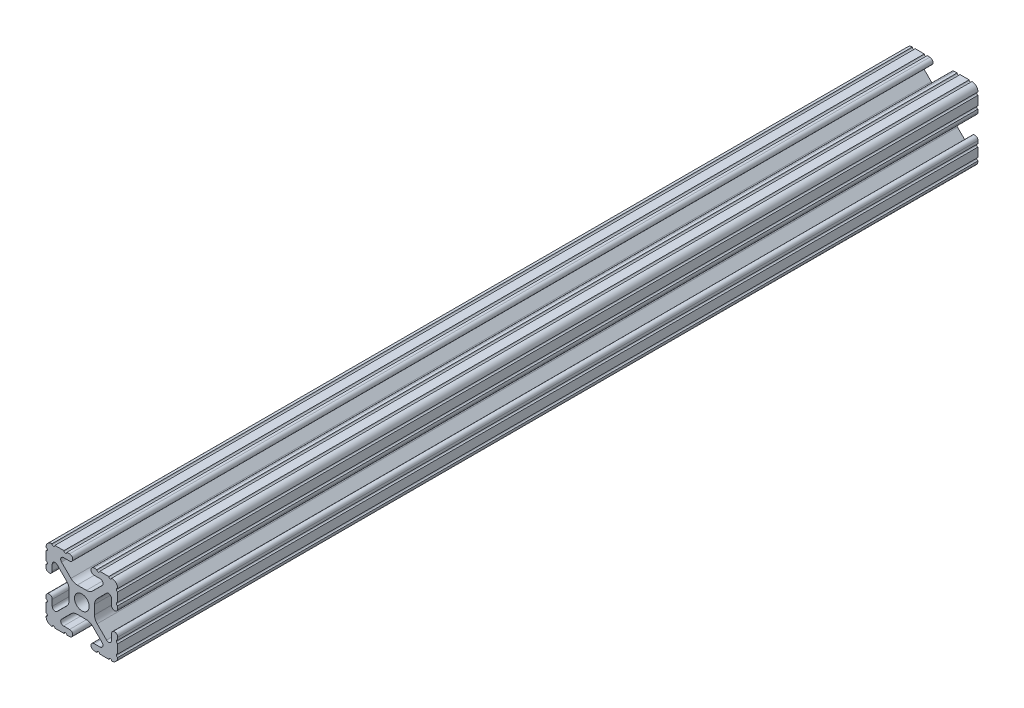
SolidWorks part; units mm, degrees
ref_plane "Front Plane" through (0, 0, 0) normal (0, 0, 1) x (1, 0, 0)
ref_plane "Top Plane" through (0, 0, 0) normal (0, 1, 0) x (1, 0, 0)
ref_plane "Right Plane" through (0, 0, 0) normal (1, 0, 0) x (0, 0, -1)
ref_plane "Plane1" through (0, 0, -25.4) normal (0, 0, -1) x (-1, 0, 0)
sketch "Sketch1" plane through (0, 0, -25.4) normal (0, 0, -1) x (-1, 0, 0)
  line L0 (12.7, -9.5504) -> (12.7, -6.3331)
  line L1 (12.7, -5.3171) -> (12.7, -4.3434)
  line L2 (10.4902, -4.3434) -> (10.4902, -6.4748)
  line L3 (8.7558, -7.1932) -> (5.4257, -3.8632)
  line L4 (4.4958, -1.6181) -> (4.4958, 1.6181)
  line L5 (5.4257, 3.8632) -> (8.7558, 7.1932)
  line L6 (10.4902, 6.4748) -> (10.4902, 4.3434)
  line L7 (12.7, 4.3434) -> (12.7, 5.3171)
  line L8 (12.7, 6.3331) -> (12.7, 9.5504)
  line L9 (9.5504, 12.7) -> (6.3331, 12.7)
  line L10 (5.3171, 12.7) -> (4.3434, 12.7)
  line L11 (4.3434, 10.4902) -> (6.4748, 10.4902)
  line L12 (7.1932, 8.7558) -> (3.8632, 5.4257)
  line L13 (1.6181, 4.4958) -> (-1.6181, 4.4958)
  line L14 (-3.8632, 5.4257) -> (-7.1932, 8.7558)
  line L15 (-6.4748, 10.4902) -> (-4.3434, 10.4902)
  line L16 (-4.3434, 12.7) -> (-5.3171, 12.7)
  line L17 (-6.3331, 12.7) -> (-9.5504, 12.7)
  line L18 (-12.7, 9.5504) -> (-12.7, 6.3331)
  line L19 (-12.7, 5.3171) -> (-12.7, 4.3434)
  line L20 (-10.4902, 4.3434) -> (-10.4902, 6.4748)
  line L21 (-8.7558, 7.1932) -> (-5.4257, 3.8632)
  line L22 (-4.4958, 1.6181) -> (-4.4958, -1.6181)
  line L23 (-5.4257, -3.8632) -> (-8.7558, -7.1932)
  line L24 (-10.4902, -6.4748) -> (-10.4902, -4.3434)
  line L25 (-12.7, -4.3434) -> (-12.7, -5.3171)
  line L26 (-12.7, -6.3331) -> (-12.7, -9.5504)
  line L27 (-9.5504, -12.7) -> (-6.3331, -12.7)
  line L28 (-5.3171, -12.7) -> (-4.3434, -12.7)
  line L29 (-4.3434, -10.4902) -> (-6.4748, -10.4902)
  line L30 (-7.1932, -8.7558) -> (-3.8632, -5.4257)
  line L31 (-1.6181, -4.4958) -> (1.6181, -4.4958)
  line L32 (3.8632, -5.4257) -> (7.1932, -8.7558)
  line L33 (6.4748, -10.4902) -> (4.3434, -10.4902)
  line L34 (4.3434, -12.7) -> (5.3171, -12.7)
  line L35 (6.3331, -12.7) -> (9.5504, -12.7)
  arc A0 (12.6998, -10.5664) -> (12.7, -9.5504) centre (12.7, -10.0584) cw
  arc A1 (12.7, -6.3331) -> (12.7, -5.3171) centre (12.7, -5.8251) cw
  arc A2 (12.7, -4.3434) -> (10.4902, -4.3434) centre (11.5951, -4.3434) ccw
  arc A3 (10.4902, -6.4748) -> (8.7558, -7.1932) centre (9.4742, -6.4748) cw
  arc A4 (5.4257, -3.8632) -> (4.4958, -1.6181) centre (7.6708, -1.6181) cw
  arc A5 (4.4958, 1.6181) -> (5.4257, 3.8632) centre (7.6708, 1.6181) cw
  arc A6 (8.7558, 7.1932) -> (10.4902, 6.4748) centre (9.4742, 6.4748) cw
  arc A7 (10.4902, 4.3434) -> (12.7, 4.3434) centre (11.5951, 4.3434) ccw
  arc A8 (12.7, 5.3171) -> (12.7, 6.3331) centre (12.7, 5.8251) cw
  arc A9 (12.7, 9.5504) -> (12.6998, 10.5664) centre (12.7, 10.0584) cw
  arc A10 (12.6998, 10.5664) -> (10.5664, 12.6998) centre (10.5918, 10.5918) ccw
  arc A11 (10.5664, 12.6998) -> (9.5504, 12.7) centre (10.0584, 12.7) cw
  arc A12 (6.3331, 12.7) -> (5.3171, 12.7) centre (5.8251, 12.7) cw
  arc A13 (4.3434, 12.7) -> (4.3434, 10.4902) centre (4.3434, 11.5951) ccw
  arc A14 (6.4748, 10.4902) -> (7.1932, 8.7558) centre (6.4748, 9.4742) cw
  arc A15 (3.8632, 5.4257) -> (1.6181, 4.4958) centre (1.6181, 7.6708) cw
  arc A16 (-1.6181, 4.4958) -> (-3.8632, 5.4257) centre (-1.6181, 7.6708) cw
  arc A17 (-7.1932, 8.7558) -> (-6.4748, 10.4902) centre (-6.4748, 9.4742) cw
  arc A18 (-4.3434, 10.4902) -> (-4.3434, 12.7) centre (-4.3434, 11.5951) ccw
  arc A19 (-5.3171, 12.7) -> (-6.3331, 12.7) centre (-5.8251, 12.7) cw
  arc A20 (-9.5504, 12.7) -> (-10.5664, 12.6998) centre (-10.0584, 12.7) cw
  arc A21 (-10.5664, 12.6998) -> (-12.6998, 10.5664) centre (-10.5918, 10.5918) ccw
  arc A22 (-12.6998, 10.5664) -> (-12.7, 9.5504) centre (-12.7, 10.0584) cw
  arc A23 (-12.7, 6.3331) -> (-12.7, 5.3171) centre (-12.7, 5.8251) cw
  arc A24 (-12.7, 4.3434) -> (-10.4902, 4.3434) centre (-11.5951, 4.3434) ccw
  arc A25 (-10.4902, 6.4748) -> (-8.7558, 7.1932) centre (-9.4742, 6.4748) cw
  arc A26 (-5.4257, 3.8632) -> (-4.4958, 1.6181) centre (-7.6708, 1.6181) cw
  arc A27 (-4.4958, -1.6181) -> (-5.4257, -3.8632) centre (-7.6708, -1.6181) cw
  arc A28 (-8.7558, -7.1932) -> (-10.4902, -6.4748) centre (-9.4742, -6.4748) cw
  arc A29 (-10.4902, -4.3434) -> (-12.7, -4.3434) centre (-11.5951, -4.3434) ccw
  arc A30 (-12.7, -5.3171) -> (-12.7, -6.3331) centre (-12.7, -5.8251) cw
  arc A31 (-12.7, -9.5504) -> (-12.6998, -10.5664) centre (-12.7, -10.0584) cw
  arc A32 (-12.6998, -10.5664) -> (-10.5664, -12.6998) centre (-10.5918, -10.5918) ccw
  arc A33 (-10.5664, -12.6998) -> (-9.5504, -12.7) centre (-10.0584, -12.7) cw
  arc A34 (-6.3331, -12.7) -> (-5.3171, -12.7) centre (-5.8251, -12.7) cw
  arc A35 (-4.3434, -12.7) -> (-4.3434, -10.4902) centre (-4.3434, -11.5951) ccw
  arc A36 (-6.4748, -10.4902) -> (-7.1932, -8.7558) centre (-6.4748, -9.4742) cw
  arc A37 (-3.8632, -5.4257) -> (-1.6181, -4.4958) centre (-1.6181, -7.6708) cw
  arc A38 (1.6181, -4.4958) -> (3.8632, -5.4257) centre (1.6181, -7.6708) cw
  arc A39 (7.1932, -8.7558) -> (6.4748, -10.4902) centre (6.4748, -9.4742) cw
  arc A40 (4.3434, -10.4902) -> (4.3434, -12.7) centre (4.3434, -11.5951) ccw
  arc A41 (5.3171, -12.7) -> (6.3331, -12.7) centre (5.8251, -12.7) cw
  arc A42 (9.5504, -12.7) -> (10.5664, -12.6998) centre (10.0584, -12.7) cw
  arc A43 (10.5664, -12.6998) -> (12.6998, -10.5664) centre (10.5918, -10.5918) ccw
  circle A44 centre (0, 0) radius 2.6035
extrude "Boss-Extrude1" add sketch "Sketch1" along normal blind 304.8
